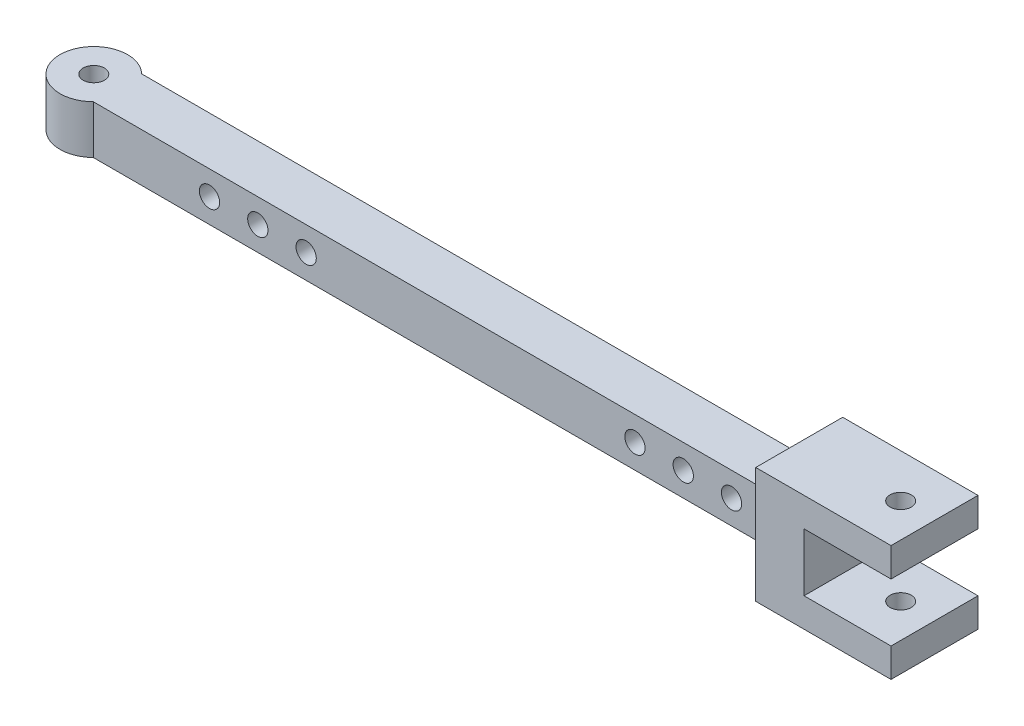
SolidWorks part; units mm, degrees
ref_plane "Front Plane" through (0, 0, 0) normal (0, 0, 1) x (1, 0, 0)
ref_plane "Top Plane" through (0, 0, 0) normal (0, 1, 0) x (1, 0, 0)
ref_plane "Right Plane" through (0, 0, 0) normal (1, 0, 0) x (0, 0, -1)
sketch "Sketch1" plane through (0, 0, 0) normal (0, 1, 0) x (1, 0, 0)
  line L1 (-40, 2.5) -> (40, 2.5)
  line L2 (-40, 2.5) -> (-40, -2.5)
  line L3 (-40, -2.5) -> (40, -2.5)
  line L4 (40, 2.5) -> (40, -2.5)
  line L5 (-40, 2.5) -> (40, -2.5) construction
  line L6 (-40, -2.5) -> (40, 2.5) construction
  point P0 (0, 0)
  dimension "D1" = 5
  dimension "D2" = 80
extrude "Boss-Extrude1" add sketch "Sketch1" along normal blind 5
sketch "Sketch7" plane through (0, 5, 0) normal (0, 1, 0) x (1, 0, 0)
  line L0 (40, -2.5) -> (40, 2.5) construction
  line L1 (33, 4.5) -> (47, 4.5)
  line L2 (33, 4.5) -> (33, -4.5)
  line L3 (33, -4.5) -> (47, -4.5)
  line L4 (47, 4.5) -> (47, -4.5)
  line L5 (33, 4.5) -> (47, -4.5) construction
  line L6 (33, -4.5) -> (47, 4.5) construction
  point P0 (40, 0)
  dimension "D1" = 9
  dimension "D2" = 14
extrude "Boss-Extrude4" add sketch "Sketch7" against normal blind 12 from offset 3.5
sketch "Sketch8" plane through (0, 5, 0) normal (0, 1, 0) x (1, 0, 0)
  line L0 (33, 2.5) -> (25, 2.5) construction
  line L1 (25, 2.5) -> (25, -2.5) construction
  line L2 (25, -2.5) -> (33, -2.5) construction
sketch "Sketch9" plane through (0, 8.5, 0) normal (0, 1, 0) x (1, 0, 0)
  line L0 (33, -4.5) -> (47, -4.5) construction
  line L1 (47, 4.5) -> (38, 4.5)
  line L2 (47, 4.5) -> (47, -4.5)
  line L3 (47, -4.5) -> (38, -4.5)
  line L4 (38, 4.5) -> (38, -4.5)
  dimension "D1" = 9
extrude "Cut-Extrude5" cut sketch "Sketch9" against normal blind 6 from offset 3 offset against normal yes
sketch "Sketch10" plane through (0, 8.5, 0) normal (0, 1, 0) x (1, 0, 0)
  line L0 (38, 4.5) -> (38, -4.5) construction
  line L1 (47, 4.5) -> (33, 4.5) construction
  line L2 (33, -4.5) -> (47, -4.5) construction
  line L3 (47, -4.5) -> (47, 4.5) construction
  dimension "D1" = 9
sketch "Sketch11" plane through (0, 8.5, 0) normal (0, 1, 0) x (1, 0, 0)
  line L0 (47, -4.5) -> (47, 4.5) construction
  circle A0 centre (43.5, 0) radius 1.1
  dimension "D1" = 3.5
  dimension "D2" = 2.2
extrude "Cut-Extrude6" cut sketch "Sketch11" against normal blind 12
sketch "Sketch15" plane through (0, 5, 0) normal (0, 1, 0) x (1, 0, 0)
  line L0 (-40, 2.5) -> (-40, -2.5) construction
  circle A0 centre (-40, 0) radius 1.1
sketch "Sketch16" plane through (0, 5, 0) normal (0, 1, 0) x (1, 0, 0)
  circle A0 centre (-40, 0) radius 3.5
extrude "Boss-Extrude7" add sketch "Sketch16" against normal blind 5 contours A0
extrude "Cut-Extrude9" cut sketch "Sketch15" against normal blind 5
sketch "Sketch18" plane through (0, 0, 2.5) normal (0, 0, 1) x (1, 0, 0)
  line L0 (-40.5253, 5) -> (-40.5253, 0) construction
  line L1 (-37.5505, 5) -> (-43.5, 5) construction
  line L2 (-43.5, 0) -> (-37.5505, 0) construction
  line L3 (43.5, 8.5) -> (43.5, -3.5) construction
  line L4 (33, 8.5) -> (47, 8.5) construction
  line L5 (33, -3.5) -> (47, -3.5) construction
  line L6 (47, 5.5) -> (47, 8.5) construction
  line L7 (-37.5505, 5) -> (33, 5) construction
  line L8 (25, 5) -> (33, 5) construction
  circle A0 centre (-20.5253, 2.5) radius 1.05
  circle A1 centre (23.5, 2.5) radius 1.05
  circle A2 centre (-25.5253, 2.5) radius 1.05
  circle A3 centre (-15.5253, 2.5) radius 1.05
  circle A4 centre (18.5, 2.5) radius 1.05
  circle A5 centre (28.5, 2.5) radius 1.05
  dimension "D1" = 20
  dimension "D2" = 20
  dimension "D4" = 2.5
  dimension "D5" = 2.5
  dimension "D6" = 5
  dimension "D7" = 5
  dimension "D8" = 5
  dimension "D9" = 5
  dimension "D3" = 3.5
extrude "Cut-Extrude10" cut sketch "Sketch18" against normal blind 5
